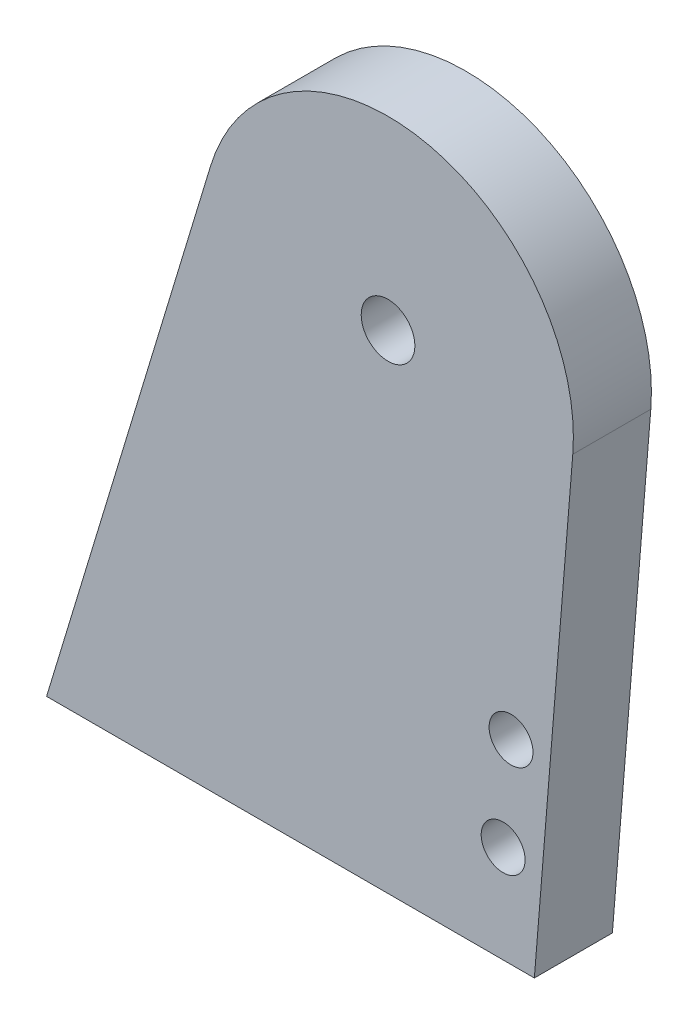
SolidWorks part; units mm, degrees
material "5052-O"
ref_plane "정면" through (0, 0, 0) normal (0, 0, 1) x (1, 0, 0)
ref_plane "윗면" through (0, 0, 0) normal (0, 1, 0) x (1, 0, 0)
ref_plane "우측면" through (0, 0, 0) normal (1, 0, 0) x (0, 0, -1)
sketch "스케치1" plane through (0, 0, 0) normal (0, 0, 1) x (1, 0, 0)
  line L0 (0, 0) -> (50, 0)
  line L1 (50, 0) -> (53.9376, 48.4613)
  line L2 (0, 0) -> (16.8161, 55.5087)
  circle A0 centre (35, 50) radius 19
  dimension "D1" = 38
  dimension "D2" = 50
  dimension "D3" = 50
  dimension "D5" = 15
extrude "보스-돌출1" add sketch "스케치1" along normal blind 8
hole_wizard "M4 여유 구멍1" positions "스케치2" profile "스케치3" hole size "M4" standard "ISO" end condition up to next
sketch "스케치2" plane through (0, 0, 8) normal (0, 0, 1) x (1, 0, 0)
  line L0 (47.6092, 19.9672) -> (46.7993, 10)
  line L2 (50, 0) -> (53.9376, 48.4613) construction
  line L3 (0, 0) -> (50, 0) construction
  point P0 (46.7993, 10)
  point P2 (47.6092, 19.9672)
  dimension "D1" = 10
  dimension "D2" = 4
  dimension "D3" = 10
sketch "스케치3" plane through (46.7993, 10, 8) normal (1, 0, 0) x (0, -1, 0)
  line L0 (0, 0) -> (0, 8)
  line L1 (0, 8) -> (2.25, 8)
  line L2 (2.25, 8) -> (2.25, 0)
  line L5 (2.25, 0) -> (0, 0)
  line L11 (0, -6.35) -> (0, 107.95) construction
  dimension "관통 구멍 지름" = 4.5
  dimension "관통 구멍 깊이" = 8
hole_wizard "M3 나사 구멍1" positions "스케치4" profile "스케치5" tap size "M3" standard "ISO"
sketch "스케치4" plane through (0, 0, 0) normal (0, -1, 0) x (-1, 0, 0)
  line L0 (-10, -4) -> (-40, -4)
  line L2 (0, 0) -> (-50, 0) construction
  line L3 (-50, -8) -> (-50, 0) construction
  point P0 (-10, -4)
  point P2 (-40, -4)
  point P8 (-25, -4)
  point P11 (-25, 0)
  point P14 (-50, -4)
  dimension "D1" = 30
sketch "스케치5" plane through (10, 0, 4) normal (1, 0, 0) x (0, 0, -1)
  line L0 (0, 0) -> (0, 9.2511)
  line L1 (0, 9.2511) -> (1.25, 8.5)
  line L2 (1.25, 8.5) -> (1.25, 0.275)
  line L3 (1.25, 0.275) -> (1.525, 0)
  line L5 (1.525, 0) -> (0, 0)
  line L6 (-1.25, 0.275) -> (-1.525, 0) construction
  line L10 (0, 9.2511) -> (-1.25, 8.5) construction
  line L11 (0, -6.35) -> (0, 107.95) construction
  dimension "탭 드릴 지름" = 2.5
  dimension "탭 드릴 깊이" = 8.5
  dimension "표면 카운터싱크 지름" = 3.05
  dimension "표면 카운터싱크 각도" = 90
  dimension "드릴 각도" = 118
cosmetic thread "구멍 나사산1" parameters "D1"=6, "D2"=3
cosmetic thread "구멍 나사산2" parameters "D1"=6, "D2"=3
hole_wizard "M5 여유 구멍1" positions "스케치6" profile "스케치7" hole size "M5" standard "ISO" end condition through all
sketch "스케치6" plane through (0, 0, 0) normal (0, 0, -1) x (-1, 0, 0)
  point P0 (-35, 50)
sketch "스케치7" plane through (35, 50, 0) normal (1, 0, 0) x (0, 1, 0)
  line L0 (0, 0) -> (0, 8)
  line L1 (0, 8) -> (2.75, 8)
  line L2 (2.75, 8) -> (2.75, 0)
  line L5 (2.75, 0) -> (0, 0)
  line L11 (0, -6.35) -> (0, 107.95) construction
  dimension "관통 구멍 지름" = 5.5
  dimension "관통 구멍 깊이" = 8
